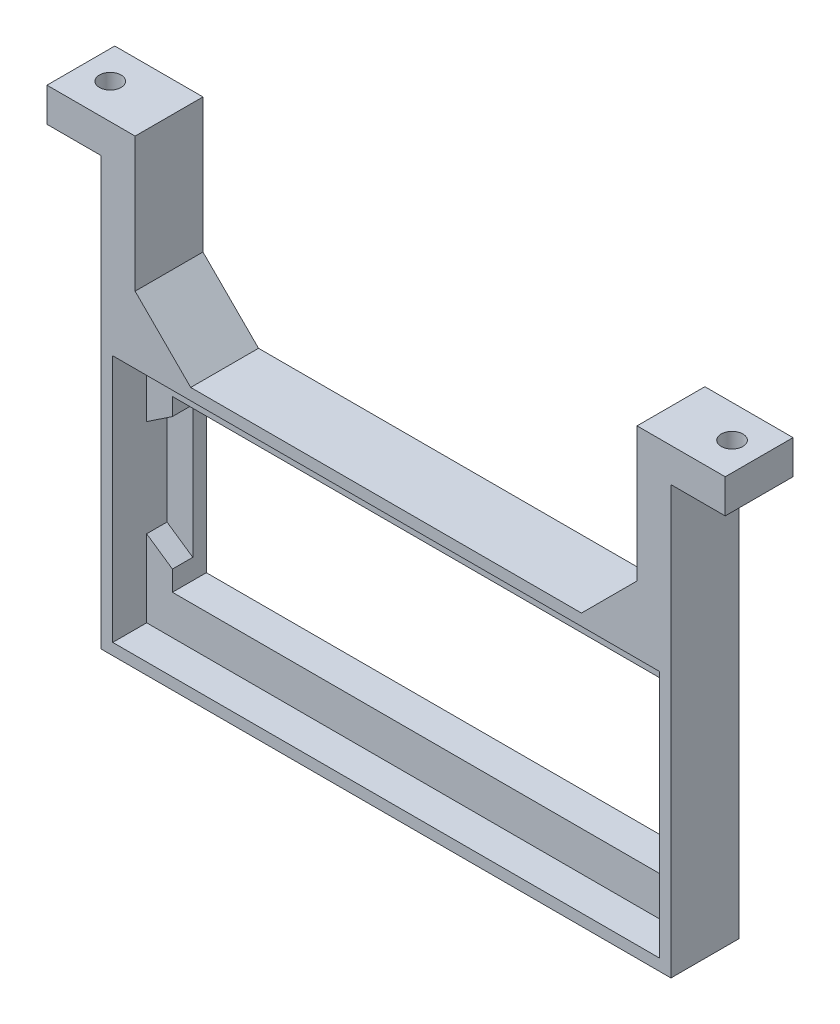
SolidWorks part; units mm, degrees
ref_plane "前视基准面" through (0, 0, 0) normal (0, 0, 1) x (1, 0, 0)
ref_plane "上视基准面" through (0, 0, 0) normal (0, 1, 0) x (1, 0, 0)
ref_plane "右视基准面" through (0, 0, 0) normal (1, 0, 0) x (0, 0, -1)
sketch "草图1" plane through (0, 0, 0) normal (0, 0, 1) x (1, 0, 0)
  line L0 (0, 40) -> (0, 63)
  line L1 (0, 0) -> (84, 0)
  line L2 (0, 0) -> (0, 40)
  line L3 (13.1941, 40) -> (70.8059, 40)
  line L4 (84, 0) -> (84, 40)
  line L5 (0, 63) -> (-8, 63)
  line L6 (-8, 63) -> (-8, 68)
  line L7 (-8, 68) -> (5, 68)
  line L8 (5, 68) -> (5, 48.1941)
  line L9 (42, 40) -> (42, 66.0238) construction
  line L10 (79, 68) -> (79, 48.1941)
  line L11 (92, 68) -> (79, 68)
  line L12 (92, 63) -> (92, 68)
  line L13 (84, 63) -> (92, 63)
  line L14 (84, 40) -> (84, 63)
  line L15 (5, 48.1941) -> (13.1941, 40)
  line L16 (79, 48.1941) -> (70.8059, 40)
  dimension "D1" = 84
  dimension "D2" = 40
  dimension "D3" = 5
  dimension "D4" = 5
  dimension "D5" = 8
extrude "凸台-拉伸1" add sketch "草图1" along normal blind 10
sketch "草图2" plane through (0, 0, 10) normal (0, 0, 1) x (1, 0, 0)
  line L0 (0, 63) -> (0, 0) construction
  line L1 (1.7, 38.3) -> (82.3, 38.3)
  line L2 (1.7, 38.3) -> (1.7, 1.7)
  line L3 (1.7, 1.7) -> (82.3, 1.7)
  line L4 (82.3, 38.3) -> (82.3, 1.7)
  line L5 (0, 0) -> (84, 0) construction
  dimension "D1" = 80.6
  dimension "D2" = 1.7
  dimension "D3" = 36.6
  dimension "D4" = 1.7
extrude "切除-拉伸1" cut sketch "草图2" against normal blind 5
sketch "草图3" plane through (0, 0, 5) normal (0, 0, 1) x (1, 0, 0)
  line L1 (5.5, 32.5) -> (78.5, 32.5)
  line L2 (5.5, 32.5) -> (5.5, 7.5)
  line L3 (5.5, 7.5) -> (78.5, 7.5)
  line L4 (78.5, 32.5) -> (78.5, 7.5)
  line L6 (42, 38.3) -> (42, 19.5524) construction
  line L7 (82.3, 38.3) -> (1.7, 38.3) construction
  line L8 (1.7, 20) -> (25.9471, 20) construction
  line L9 (1.7, 38.3) -> (1.7, 1.7) construction
  dimension "D1" = 73
  dimension "D2" = 25
extrude "切除-拉伸2" cut sketch "草图3" against normal through all
sketch "草图4" plane through (0, 0, 5) normal (0, 0, 1) x (1, 0, 0)
  line L0 (77.0173, 30.9311) -> (82.3, 27.39)
  line L1 (82.3, 1.7) -> (82.3, 38.3) construction
  line L2 (82.3, 27.39) -> (82.3, 13.0683)
  line L3 (82.3, 13.0683) -> (77.0173, 9.4485)
  line L4 (77.0173, 9.4485) -> (77.0173, 30.9311)
  line L5 (42, 32.5) -> (42, 20.3865) construction
  line L6 (78.5, 32.5) -> (5.5, 32.5) construction
  line L7 (6.9827, 9.4485) -> (6.9827, 30.9311)
  line L8 (1.7, 13.0683) -> (6.9827, 9.4485)
  line L9 (1.7, 27.39) -> (1.7, 13.0683)
  line L10 (6.9827, 30.9311) -> (1.7, 27.39)
extrude "切除-拉伸3" cut sketch "草图4" against normal blind 3
sketch "草图5" plane through (0, 63, 0) normal (0, -1, 0) x (1, 0, 0)
  line L0 (42, 10) -> (42, 0) construction
  line L1 (0, 10) -> (84, 10) construction
  line L2 (0, 0) -> (84, 0) construction
  circle A0 centre (87.8375, 4.8309) radius 1.6
  circle A1 centre (-3.8375, 4.8309) radius 1.6
  dimension "D1" = 3.2
extrude "切除-拉伸4" cut sketch "草图5" against normal through all
